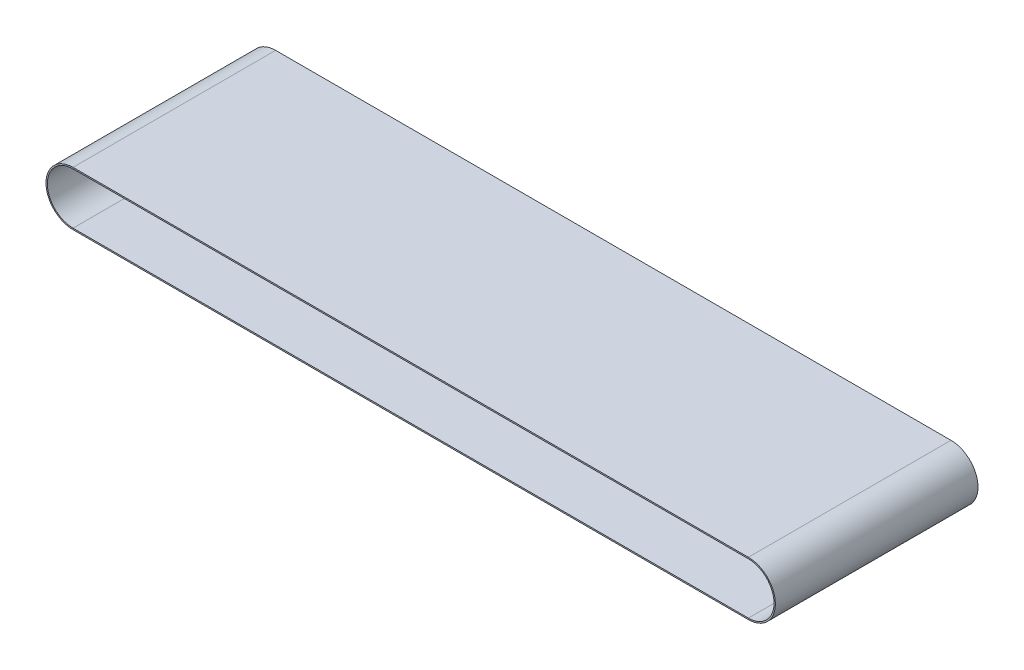
SolidWorks part; units mm, degrees
material "PVC Rigid 刚性聚氯乙烯"
ref_plane "前视基准面" through (0, 0, 0) normal (0, 0, 1) x (1, 0, 0)
ref_plane "上视基准面" through (0, 0, 0) normal (0, 1, 0) x (1, 0, 0)
ref_plane "右视基准面" through (0, 0, 0) normal (1, 0, 0) x (0, 0, -1)
other "Configuration Table"
sketch "草图1" plane through (0, 0, 0) normal (0, 0, 1) x (1, 0, 0)
  line L0 (-500, 0) -> (500, 0) construction
  line L3 (-500, 38) -> (500, 38)
  line L4 (-500, -38) -> (500, -38)
  arc A2 (-500, 38) -> (-500, -38) centre (-500, 0) ccw
  arc A3 (500, -38) -> (500, 38) centre (500, 0) ccw
  point P3 (0, 0)
  dimension "D1" = 1000
  dimension "D2" = 76
extrude "拉伸-薄壁1" add sketch "草图1" along normal mid plane 300 thin thin type one direction wall 2
equation "\"长\"= 1000mm"
equation "\"宽\"= 300mm"
equation "\"高\"= 500mm"
equation "\"D1@草图1\"=\"长\""
